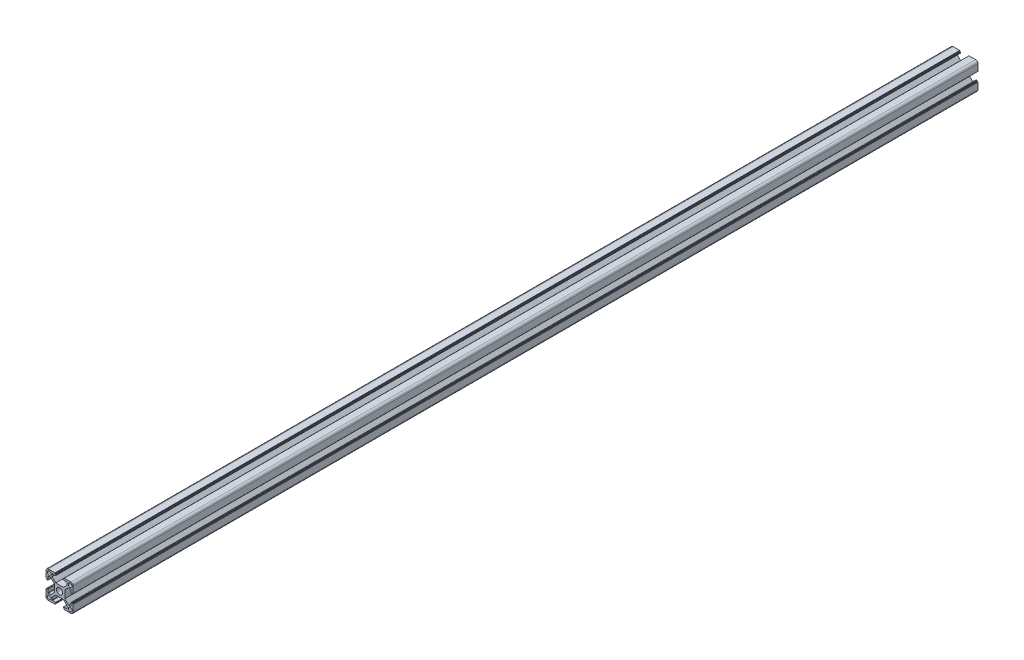
SolidWorks part; units mm, degrees
ref_plane "前视基准面" through (0, 0, 0) normal (0, 0, 1) x (1, 0, 0)
ref_plane "上视基准面" through (0, 0, 0) normal (0, 1, 0) x (1, 0, 0)
ref_plane "右视基准面" through (0, 0, 0) normal (1, 0, 0) x (0, 0, -1)
sketch "草图1" plane through (0, 0, 0) normal (0, 0, 1) x (1, 0, 0)
  line L0 (5.3943, 3.7989) -> (9.3999, 7.8045)
  line L1 (9.3999, 7.8045) -> (12.0943, 7.8045)
  line L2 (12.3943, 7.5045) -> (12.3943, 3.9545)
  line L3 (12.6943, 3.6545) -> (13.5943, 3.6545)
  line L4 (13.5943, 3.6545) -> (13.5943, 4.4545)
  line L5 (13.7943, 4.6545) -> (14.5943, 4.6545)
  line L6 (14.5943, 4.6545) -> (14.5943, 12.0545)
  line L7 (12.0943, 14.5545) -> (4.6943, 14.5545)
  line L8 (4.6943, 14.5545) -> (4.6943, 13.7545)
  line L9 (4.4943, 13.5545) -> (3.6943, 13.5545)
  line L10 (3.6943, 13.5545) -> (3.6943, 12.6545)
  line L11 (3.9943, 12.3545) -> (7.5443, 12.3545)
  line L12 (7.8443, 12.0545) -> (7.8443, 9.3602)
  line L13 (7.8443, 9.3602) -> (3.8386, 5.3545)
  line L14 (3.8386, 5.3545) -> (-4.6501, 5.3545)
  line L15 (-4.6501, 5.3545) -> (-8.6557, 9.3602)
  line L16 (-8.6557, 9.3602) -> (-8.6557, 12.0545)
  line L17 (-8.3557, 12.3545) -> (-4.8057, 12.3545)
  line L18 (-4.5057, 12.6545) -> (-4.5057, 13.5545)
  line L19 (-4.5057, 13.5545) -> (-5.3057, 13.5545)
  line L20 (-5.5057, 13.7545) -> (-5.5057, 14.5545)
  line L21 (-5.5057, 14.5545) -> (-12.9057, 14.5545)
  line L22 (-15.4057, 12.0545) -> (-15.4057, 4.6545)
  line L23 (-15.4057, 4.6545) -> (-14.6057, 4.6545)
  line L24 (-14.4057, 4.4545) -> (-14.4057, 3.6545)
  line L25 (-14.4057, 3.6545) -> (-13.5057, 3.6545)
  line L26 (-13.2057, 3.9545) -> (-13.2057, 7.5045)
  line L27 (-12.9057, 7.8045) -> (-10.2114, 7.8045)
  line L28 (-10.2114, 7.8045) -> (-6.2057, 3.7989)
  line L29 (-6.2057, 3.7989) -> (-6.2057, -4.6898)
  line L30 (-6.2057, -4.6898) -> (-10.2114, -8.6955)
  line L31 (-10.2114, -8.6955) -> (-12.9057, -8.6955)
  line L32 (-13.2057, -8.3955) -> (-13.2057, -4.8455)
  line L33 (-13.5057, -4.5455) -> (-14.4057, -4.5455)
  line L34 (-14.4057, -4.5455) -> (-14.4057, -5.3455)
  line L35 (-14.6057, -5.5455) -> (-15.4057, -5.5455)
  line L36 (-15.4057, -5.5455) -> (-15.4057, -12.9455)
  line L37 (-12.9057, -15.4455) -> (-5.5057, -15.4455)
  line L38 (-5.5057, -15.4455) -> (-5.5057, -14.6455)
  line L39 (-5.3057, -14.4455) -> (-4.5057, -14.4455)
  line L40 (-4.5057, -14.4455) -> (-4.5057, -13.5455)
  line L41 (-4.8057, -13.2455) -> (-8.3557, -13.2455)
  line L42 (-8.6557, -12.9455) -> (-8.6557, -10.2511)
  line L43 (-8.6557, -10.2511) -> (-4.6501, -6.2455)
  line L44 (-4.6501, -6.2455) -> (3.8386, -6.2455)
  line L45 (3.8386, -6.2455) -> (7.8443, -10.2511)
  line L46 (7.8443, -10.2511) -> (7.8443, -12.9455)
  line L47 (7.5443, -13.2455) -> (3.9943, -13.2455)
  line L48 (3.6943, -13.5455) -> (3.6943, -14.4455)
  line L49 (3.6943, -14.4455) -> (4.4943, -14.4455)
  line L50 (4.6943, -14.6455) -> (4.6943, -15.4455)
  line L51 (4.6943, -15.4455) -> (12.0943, -15.4455)
  line L52 (14.5943, -12.9455) -> (14.5943, -5.5455)
  line L53 (14.5943, -5.5455) -> (13.7943, -5.5455)
  line L54 (13.5943, -5.3455) -> (13.5943, -4.5455)
  line L55 (13.5943, -4.5455) -> (12.6943, -4.5455)
  line L56 (12.3943, -4.8455) -> (12.3943, -8.3955)
  line L57 (12.0943, -8.6955) -> (9.3999, -8.6955)
  line L58 (9.3999, -8.6955) -> (5.3943, -4.6898)
  line L59 (5.3943, -4.6898) -> (5.3943, 3.7989)
  circle A0 centre (-0.4057, -0.4455) radius 3.4
  arc A1 (12.3943, 7.5045) -> (12.0943, 7.8045) centre (12.0943, 7.5045) ccw
  arc A2 (12.3943, 3.9545) -> (12.6943, 3.6545) centre (12.6943, 3.9545) ccw
  arc A3 (13.7943, 4.6545) -> (13.5943, 4.4545) centre (13.7943, 4.4545) ccw
  arc A4 (14.5943, 12.0545) -> (12.0943, 14.5545) centre (12.0943, 12.0545) ccw
  arc A5 (4.4943, 13.5545) -> (4.6943, 13.7545) centre (4.4943, 13.7545) ccw
  arc A6 (3.6943, 12.6545) -> (3.9943, 12.3545) centre (3.9943, 12.6545) ccw
  arc A7 (7.8443, 12.0545) -> (7.5443, 12.3545) centre (7.5443, 12.0545) ccw
  arc A8 (-8.3557, 12.3545) -> (-8.6557, 12.0545) centre (-8.3557, 12.0545) ccw
  arc A9 (-4.8057, 12.3545) -> (-4.5057, 12.6545) centre (-4.8057, 12.6545) ccw
  arc A10 (-5.5057, 13.7545) -> (-5.3057, 13.5545) centre (-5.3057, 13.7545) ccw
  arc A11 (-12.9057, 14.5545) -> (-15.4057, 12.0545) centre (-12.9057, 12.0545) ccw
  arc A12 (-14.4057, 4.4545) -> (-14.6057, 4.6545) centre (-14.6057, 4.4545) ccw
  arc A13 (-13.5057, 3.6545) -> (-13.2057, 3.9545) centre (-13.5057, 3.9545) ccw
  arc A14 (-12.9057, 7.8045) -> (-13.2057, 7.5045) centre (-12.9057, 7.5045) ccw
  arc A15 (-13.2057, -8.3955) -> (-12.9057, -8.6955) centre (-12.9057, -8.3955) ccw
  arc A16 (-13.2057, -4.8455) -> (-13.5057, -4.5455) centre (-13.5057, -4.8455) ccw
  arc A17 (-14.6057, -5.5455) -> (-14.4057, -5.3455) centre (-14.6057, -5.3455) ccw
  arc A18 (-15.4057, -12.9455) -> (-12.9057, -15.4455) centre (-12.9057, -12.9455) ccw
  arc A19 (-5.3057, -14.4455) -> (-5.5057, -14.6455) centre (-5.3057, -14.6455) ccw
  arc A20 (-4.5057, -13.5455) -> (-4.8057, -13.2455) centre (-4.8057, -13.5455) ccw
  arc A21 (-8.6557, -12.9455) -> (-8.3557, -13.2455) centre (-8.3557, -12.9455) ccw
  arc A22 (7.5443, -13.2455) -> (7.8443, -12.9455) centre (7.5443, -12.9455) ccw
  arc A23 (3.9943, -13.2455) -> (3.6943, -13.5455) centre (3.9943, -13.5455) ccw
  arc A24 (4.6943, -14.6455) -> (4.4943, -14.4455) centre (4.4943, -14.6455) ccw
  arc A25 (12.0943, -15.4455) -> (14.5943, -12.9455) centre (12.0943, -12.9455) ccw
  arc A26 (13.5943, -5.3455) -> (13.7943, -5.5455) centre (13.7943, -5.3455) ccw
  arc A27 (12.6943, -4.5455) -> (12.3943, -4.8455) centre (12.6943, -4.8455) ccw
  arc A28 (12.0943, -8.6955) -> (12.3943, -8.3955) centre (12.0943, -8.3955) ccw
  circle A29 centre (-12.0307, 11.1795) radius 2
  circle A30 centre (11.2193, 11.1795) radius 2
  circle A31 centre (-12.0307, -12.0705) radius 2
  circle A32 centre (11.2193, -12.0705) radius 2
extrude "凸台-拉伸1" add sketch "草图1" along normal blind 1000
